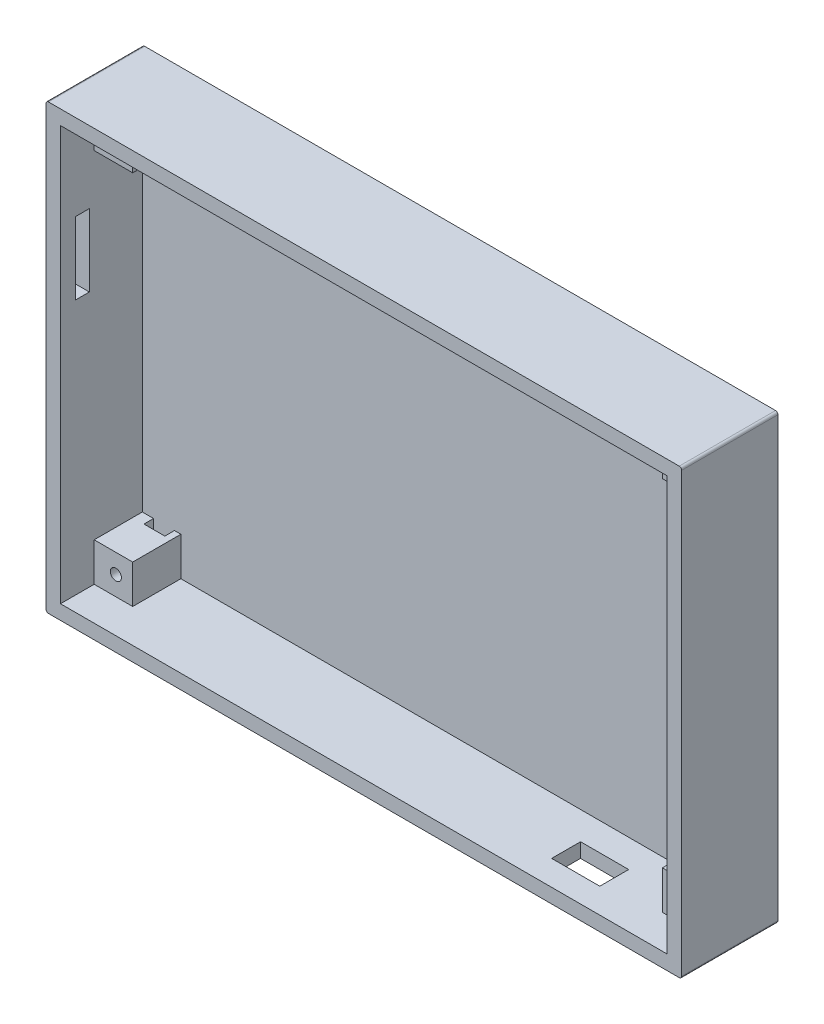
SolidWorks part; units mm, degrees
ref_plane "Plan de face" through (0, 0, 0) normal (0, 0, 1) x (1, 0, 0)
ref_plane "Plan de dessus" through (0, 0, 0) normal (0, 1, 0) x (1, 0, 0)
ref_plane "Plan de droite" through (0, 0, 0) normal (1, 0, 0) x (0, 0, -1)
sketch "Esquisse1" plane through (0, 0, 0) normal (0, 0, 1) x (1, 0, 0)
  line L3 (-32.4653, 69.6337) -> (99.5347, 69.6337)
  line L4 (-32.4653, 69.6337) -> (-32.4653, -22.3663)
  line L5 (-32.4653, -22.3663) -> (99.5347, -22.3663)
  line L6 (99.5347, 69.6337) -> (99.5347, -22.3663)
extrude "Boss.-Extru.1" add sketch "Esquisse1" along normal blind 18 and the other way blind 2
sketch "Esquisse14" plane through (0, 0, -2) normal (0, 0, -1) x (-1, 0, 0)
  line L0 (-99.5347, -22.3663) -> (-99.5347, 69.6337) construction
  line L1 (29.4653, 66.6337) -> (-96.5347, 66.6337)
  line L2 (29.4653, 66.6337) -> (29.4653, -19.3663)
  line L3 (29.4653, -19.3663) -> (-96.5347, -19.3663)
  line L4 (-96.5347, 66.6337) -> (-96.5347, -19.3663)
  line L5 (32.4653, -22.3663) -> (-99.5347, -22.3663) construction
  line L6 (32.4653, 69.6337) -> (32.4653, -22.3663) construction
  line L7 (-99.5347, 69.6337) -> (32.4653, 69.6337) construction
  dimension "D1" = 3
  dimension "D2" = 3
  dimension "D3" = 3
  dimension "D4" = 3
extrude "Enlèv. mat.-Extru.1" cut sketch "Esquisse14" against normal through all from offset 3 offset against normal yes
sketch "Esquisse15" plane through (0, 66.6337, 0) normal (0, -1, 0) x (-1, 0, 0)
  line L1 (21.4653, -11) -> (29.4653, -11)
  line L2 (21.4653, -11) -> (21.4653, -1)
  line L3 (21.4653, -1) -> (29.4653, -1)
  line L4 (29.4653, -11) -> (29.4653, -1)
extrude "Boss.-Extru.2" add sketch "Esquisse15" along normal blind 8
sketch "Esquisse16" plane through (0, 66.6337, 0) normal (0, -1, 0) x (-1, 0, 0)
  line L1 (-88.5347, -11) -> (-96.5347, -11)
  line L2 (-88.5347, -11) -> (-88.5347, -1)
  line L3 (-88.5347, -1) -> (-96.5347, -1)
  line L4 (-96.5347, -11) -> (-96.5347, -1)
extrude "Boss.-Extru.3" add sketch "Esquisse16" along normal blind 8
sketch "Esquisse17" plane through (0, -19.3663, 0) normal (0, 1, 0) x (1, 0, 0)
  line L1 (88.5347, -11) -> (96.5347, -11)
  line L2 (88.5347, -11) -> (88.5347, -1)
  line L3 (88.5347, -1) -> (96.5347, -1)
  line L4 (96.5347, -11) -> (96.5347, -1)
extrude "Boss.-Extru.4" add sketch "Esquisse17" along normal blind 8
sketch "Esquisse18" plane through (0, -19.3663, 0) normal (0, 1, 0) x (1, 0, 0)
  line L1 (-21.4653, -11) -> (-29.4653, -11)
  line L2 (-21.4653, -11) -> (-21.4653, -1)
  line L3 (-21.4653, -1) -> (-29.4653, -1)
  line L4 (-29.4653, -11) -> (-29.4653, -1)
extrude "Boss.-Extru.5" add sketch "Esquisse18" along normal blind 8
sketch "Esquisse19" plane through (0, 0, 11) normal (0, 0, 1) x (1, 0, 0)
  line L0 (96.5347, -11.3663) -> (96.5347, -19.3663) construction
  line L1 (88.5347, -19.3663) -> (96.5347, -19.3663) construction
  circle A0 centre (92.0347, -15.3663) radius 1.15
  dimension "D1" = 4.5
  dimension "D2" = 4
extrude "Enlèv. mat.-Extru.2" cut sketch "Esquisse19" against normal blind 10 contours A0
sketch "Esquisse20" plane through (0, 0, 11) normal (0, 0, 1) x (1, 0, 0)
  line L0 (96.5347, -19.3663) -> (-29.4653, -19.3663) construction
  line L1 (-29.4653, -19.3663) -> (-29.4653, 66.6337) construction
  circle A0 centre (-24.9653, -15.3663) radius 1.15
  dimension "D1" = 4
  dimension "D2" = 4.5
extrude "Enlèv. mat.-Extru.3" cut sketch "Esquisse20" against normal blind 10
sketch "Esquisse21" plane through (0, 0, 11) normal (0, 0, 1) x (1, 0, 0)
  line L0 (-29.4653, -19.3663) -> (-29.4653, 66.6337) construction
  line L1 (-29.4653, 66.6337) -> (96.5347, 66.6337) construction
  circle A0 centre (-24.9653, 61.6337) radius 1.15
  dimension "D1" = 4.5
  dimension "D2" = 5
extrude "Enlèv. mat.-Extru.4" cut sketch "Esquisse21" against normal blind 10
sketch "Esquisse22" plane through (0, 0, 11) normal (0, 0, 1) x (1, 0, 0)
  line L0 (96.5347, 66.6337) -> (96.5347, -19.3663) construction
  line L1 (-29.4653, 66.6337) -> (96.5347, 66.6337) construction
  circle A0 centre (92.0347, 61.6337) radius 1.15
  dimension "D1" = 4.5
  dimension "D2" = 5
extrude "Enlèv. mat.-Extru.5" cut sketch "Esquisse22" against normal blind 10
sketch "Esquisse23" plane through (0, 0, 11) normal (0, 0, 1) x (1, 0, 0)
  line L1 (89.8696, -14.1163) -> (89.8696, -16.6163)
  line L2 (89.8696, -16.6163) -> (92.0347, -17.8663)
  line L3 (92.0347, -17.8663) -> (94.1998, -16.6163)
  line L4 (94.1998, -16.6163) -> (94.1998, -14.1163)
  line L5 (94.1998, -14.1163) -> (92.0347, -12.8663)
  line L6 (92.0347, -12.8663) -> (89.8696, -14.1163)
  circle A0 centre (92.0347, -15.3663) radius 2.1651 construction
  circle A1 centre (92.0347, -15.3663) radius 1.15 construction
  point P10 (92.0347, -15.3663)
  point P11 (92.0347, -15.3538)
  dimension "D1" = 0
  dimension "D2" = 0
extrude "Enlèv. mat.-Extru.6" cut sketch "Esquisse23" against normal blind 2 from offset 8 offset against normal yes
sketch "Esquisse24" plane through (0, -11.3663, 0) normal (0, 1, 0) x (1, 0, 0)
  line L0 (96.5347, -1) -> (88.5347, -1) construction
  line L1 (89.8647, -3) -> (94.2047, -3)
  line L2 (89.8647, -3) -> (89.8647, -1)
  line L3 (89.8647, -1) -> (94.2047, -1)
  line L4 (94.2047, -3) -> (94.2047, -1)
  line L5 (96.5347, -11) -> (96.5347, -1) construction
  line L6 (88.5347, -1) -> (88.5347, -11) construction
  dimension "D1" = 2.33
  dimension "D2" = 1.33
extrude "Enlèv. mat.-Extru.7" cut sketch "Esquisse24" against normal blind 3
sketch "Esquisse25" plane through (0, 0, 11) normal (0, 0, 1) x (1, 0, 0)
  line L1 (-22.8002, -14.1163) -> (-24.9653, -12.8663)
  line L2 (-24.9653, -12.8663) -> (-27.1304, -14.1163)
  line L3 (-27.1304, -14.1163) -> (-27.1304, -16.6163)
  line L4 (-27.1304, -16.6163) -> (-24.9653, -17.8663)
  line L5 (-24.9653, -17.8663) -> (-22.8002, -16.6163)
  line L6 (-22.8002, -16.6163) -> (-22.8002, -14.1163)
  circle A0 centre (-24.9653, -15.3663) radius 2.1651 construction
  circle A1 centre (-24.9653, -15.3663) radius 1.15 construction
  dimension "D1" = 0
extrude "Enlèv. mat.-Extru.8" cut sketch "Esquisse25" against normal blind 2 from offset 8 offset against normal yes
sketch "Esquisse26" plane through (0, -11.3663, 0) normal (0, 1, 0) x (1, 0, 0)
  line L0 (-21.4653, -1) -> (-29.4653, -1) construction
  line L1 (-22.7953, -1) -> (-27.1353, -1)
  line L2 (-22.7953, -1) -> (-22.7953, -3)
  line L3 (-22.7953, -3) -> (-27.1353, -3)
  line L4 (-27.1353, -1) -> (-27.1353, -3)
  line L5 (-21.4653, -11) -> (-21.4653, -1) construction
  line L6 (-29.4653, -1) -> (-29.4653, -11) construction
  dimension "D1" = 1.33
  dimension "D2" = 2.33
extrude "Enlèv. mat.-Extru.9" cut sketch "Esquisse26" against normal blind 3
sketch "Esquisse27" plane through (0, 0, 11) normal (0, 0, 1) x (1, 0, 0)
  line L1 (-24.9653, 59.1337) -> (-22.8002, 60.3837)
  line L2 (-22.8002, 60.3837) -> (-22.8002, 62.8837)
  line L3 (-22.8002, 62.8837) -> (-24.9653, 64.1337)
  line L4 (-24.9653, 64.1337) -> (-27.1304, 62.8837)
  line L5 (-27.1304, 62.8837) -> (-27.1304, 60.3837)
  line L6 (-27.1304, 60.3837) -> (-24.9653, 59.1337)
  circle A0 centre (-24.9653, 61.6337) radius 2.1651 construction
  circle A1 centre (-24.9653, 61.6337) radius 1.15 construction
  dimension "D1" = 0
extrude "Enlèv. mat.-Extru.10" cut sketch "Esquisse27" against normal blind 2 from offset 8 offset against normal yes
sketch "Esquisse28" plane through (0, 58.6337, 0) normal (0, -1, 0) x (-1, 0, 0)
  line L0 (29.4653, -1) -> (21.4653, -1) construction
  line L1 (27.1353, -3) -> (22.7953, -3)
  line L2 (27.1353, -3) -> (27.1353, -1)
  line L3 (27.1353, -1) -> (22.7953, -1)
  line L4 (22.7953, -3) -> (22.7953, -1)
  line L5 (29.4653, -11) -> (29.4653, -1) construction
  line L6 (21.4653, -1) -> (21.4653, -11) construction
  point P6 (27.1353, -2)
  dimension "D1" = 2.33
  dimension "D2" = 1.33
extrude "Enlèv. mat.-Extru.11" cut sketch "Esquisse28" against normal blind 3
sketch "Esquisse29" plane through (0, 0, 11) normal (0, 0, 1) x (1, 0, 0)
  line L1 (89.8696, 60.3837) -> (92.0347, 59.1337)
  line L2 (92.0347, 59.1337) -> (94.1998, 60.3837)
  line L3 (94.1998, 60.3837) -> (94.1998, 62.8837)
  line L4 (94.1998, 62.8837) -> (92.0347, 64.1337)
  line L5 (92.0347, 64.1337) -> (89.8696, 62.8837)
  line L6 (89.8696, 62.8837) -> (89.8696, 60.3837)
  circle A0 centre (92.0347, 61.6337) radius 2.1651 construction
  circle A1 centre (92.0347, 61.6337) radius 1.15 construction
  dimension "D1" = 0
extrude "Enlèv. mat.-Extru.12" cut sketch "Esquisse29" against normal blind 2 from offset 8 offset against normal yes
sketch "Esquisse30" plane through (0, 58.6337, 0) normal (0, -1, 0) x (-1, 0, 0)
  line L0 (-88.5347, -1) -> (-96.5347, -1) construction
  line L1 (-94.2047, -3) -> (-89.8647, -3)
  line L2 (-94.2047, -3) -> (-94.2047, -1)
  line L3 (-94.2047, -1) -> (-89.8647, -1)
  line L4 (-89.8647, -3) -> (-89.8647, -1)
  line L5 (-96.5347, -1) -> (-96.5347, -11) construction
  line L6 (-88.5347, -11) -> (-88.5347, -1) construction
  dimension "D1" = 2.33
  dimension "D2" = 1.33
extrude "Enlèv. mat.-Extru.13" cut sketch "Esquisse30" against normal blind 3
sketch "Esquisse31" plane through (0, -19.3663, 0) normal (0, 1, 0) x (1, 0, 0)
  line L0 (96.5347, -18) -> (96.5347, -11) construction
  line L1 (77.3347, -12.8) -> (67.3347, -12.8)
  line L2 (77.3347, -12.8) -> (77.3347, -6.8)
  line L3 (77.3347, -6.8) -> (67.3347, -6.8)
  line L4 (67.3347, -12.8) -> (67.3347, -6.8)
  line L5 (88.5347, -11) -> (96.5347, -11) construction
  dimension "D1" = 19.2
  dimension "D2" = 1.8
extrude "Enlèv. mat.-Extru.14" cut sketch "Esquisse31" against normal blind 3
sketch "Esquisse32" plane through (-29.4653, 0, 0) normal (1, 0, 0) x (0, 0, -1)
  line L0 (-18, 66.6337) -> (-11, 66.6337) construction
  line L1 (-12, 33.7037) -> (-14.85, 33.7037)
  line L2 (-12, 33.7037) -> (-12, 48.7037)
  line L3 (-12, 48.7037) -> (-14.85, 48.7037)
  line L4 (-14.85, 33.7037) -> (-14.85, 48.7037)
  line L5 (-11, 58.6337) -> (-11, 66.6337) construction
  dimension "D1" = 17.93
  dimension "D2" = 1
extrude "Enlèv. mat.-Extru.15" cut sketch "Esquisse32" against normal blind 3
fillet "Congé1" radius 0.5 1 edges at (-32.4653, 69.6337, 8)
fillet "Congé2" radius 0.5 1 edges at (-32.4653, -22.3663, 8)
fillet "Congé3" radius 0.5 1 edges at (99.5347, -22.3663, 8)
fillet "Congé4" radius 0.5 1 edges at (99.5347, 69.6337, 8)
